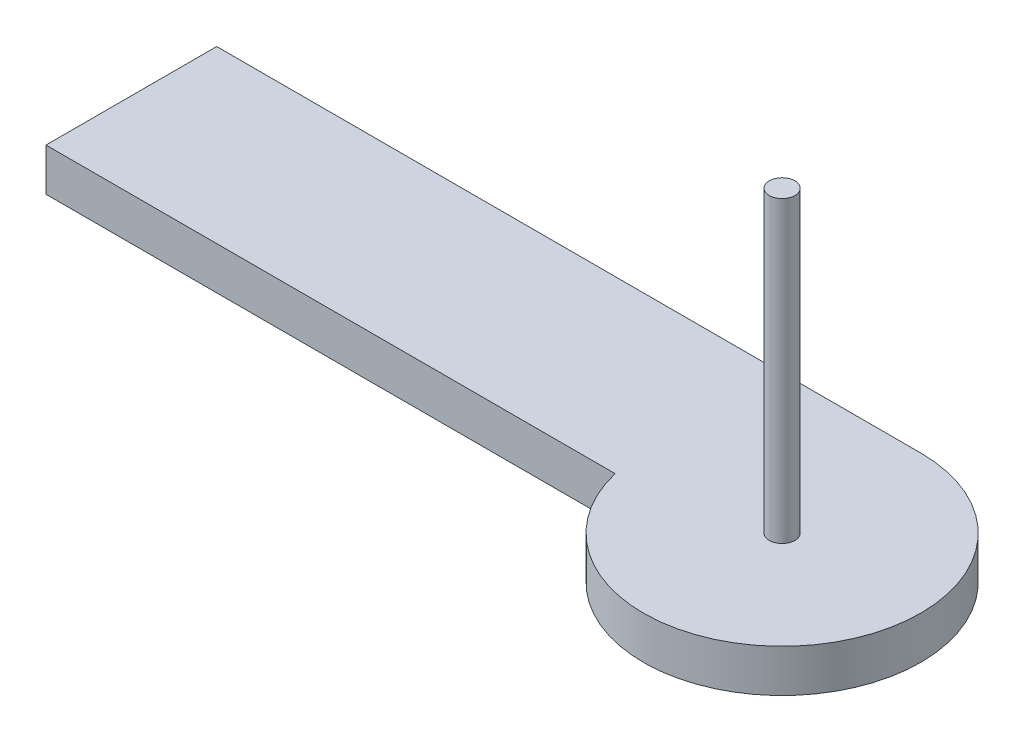
SolidWorks part; units mm, degrees
ref_plane "Front Plane" through (0, 0, 0) normal (0, 0, 1) x (1, 0, 0)
ref_plane "Top Plane" through (0, 0, 0) normal (0, 1, 0) x (1, 0, 0)
ref_plane "Right Plane" through (0, 0, 0) normal (1, 0, 0) x (0, 0, -1)
sketch "Sketch1" plane through (0, 0, 0) normal (0, 1, 0) x (1, 0, 0)
  line L0 (0, 32.5) -> (-165, 32.5)
  line L1 (-165, 32.5) -> (-165, -7.5)
  line L2 (-165, -7.5) -> (-31.6228, -7.5)
  circle A0 centre (0, 0) radius 32.5
  dimension "D1" = 65
  dimension "D2" = 165
  dimension "D3" = 40
extrude "Boss-Extrude1" add sketch "Sketch1" along normal blind 10 contours A0 L0 L1 L2 | A0
sketch "Sketch2" plane through (0, 10, 0) normal (0, 1, 0) x (1, 0, 0)
  circle A0 centre (0, 0) radius 3
  dimension "D1" = 6
extrude "Boss-Extrude2" add sketch "Sketch2" along normal blind 70
